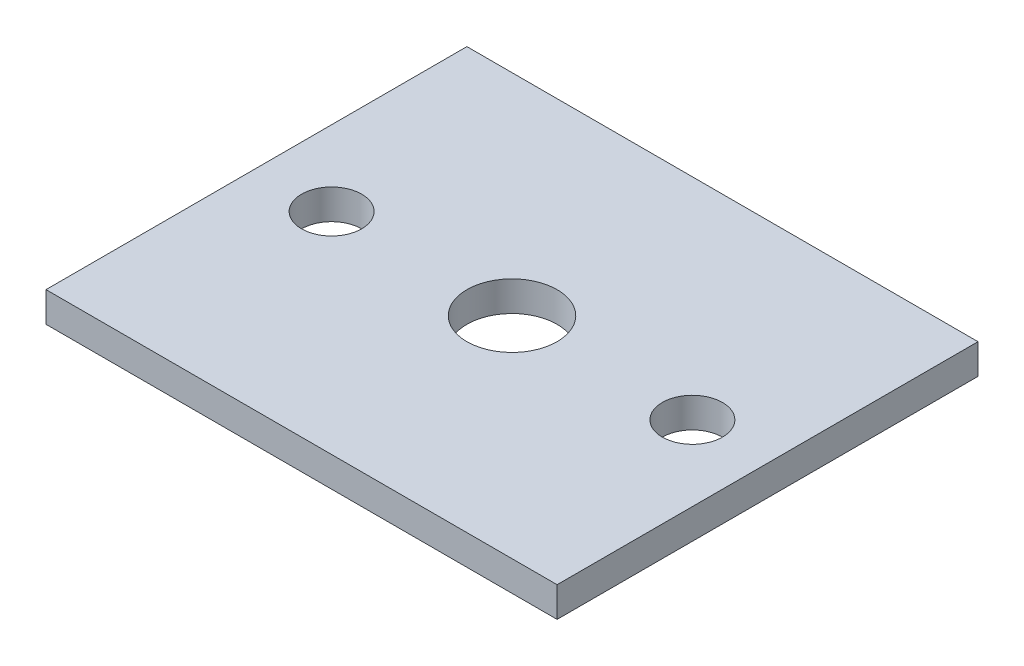
SolidWorks part; units mm, degrees
ref_plane "Front Plane" through (0, 0, 0) normal (0, 0, 1) x (1, 0, 0)
ref_plane "Top Plane" through (0, 0, 0) normal (0, 1, 0) x (1, 0, 0)
ref_plane "Right Plane" through (0, 0, 0) normal (1, 0, 0) x (0, 0, -1)
sketch "Sketch1" plane through (0, 0, 0) normal (0, 1, 0) x (1, 0, 0)
  line L1 (0, 0) -> (170, 0)
  line L2 (0, 0) -> (0, 140)
  line L3 (0, 140) -> (170, 140)
  line L4 (170, 0) -> (170, 140)
  dimension "D1" = 140
  dimension "D2" = 170
extrude "Boss-Extrude1" add sketch "Sketch1" along normal blind 10
sketch "Sketch2" plane through (0, 10, 0) normal (0, 1, 0) x (1, 0, 0)
  line L0 (0, 140) -> (0, 0) construction
  line L1 (170, 140) -> (0, 140) construction
  circle A0 centre (25, 70) radius 10
  circle A1 centre (145, 70) radius 10
  circle A2 centre (85, 70) radius 15
  dimension "D1" = 20
  dimension "D2" = 20
  dimension "D3" = 30
  dimension "D4" = 25
  dimension "D5" = 85
  dimension "D6" = 145
  dimension "D7" = 70
  dimension "D8" = 70
  dimension "D9" = 70
extrude "Cut-Extrude1" cut sketch "Sketch2" against normal through all
